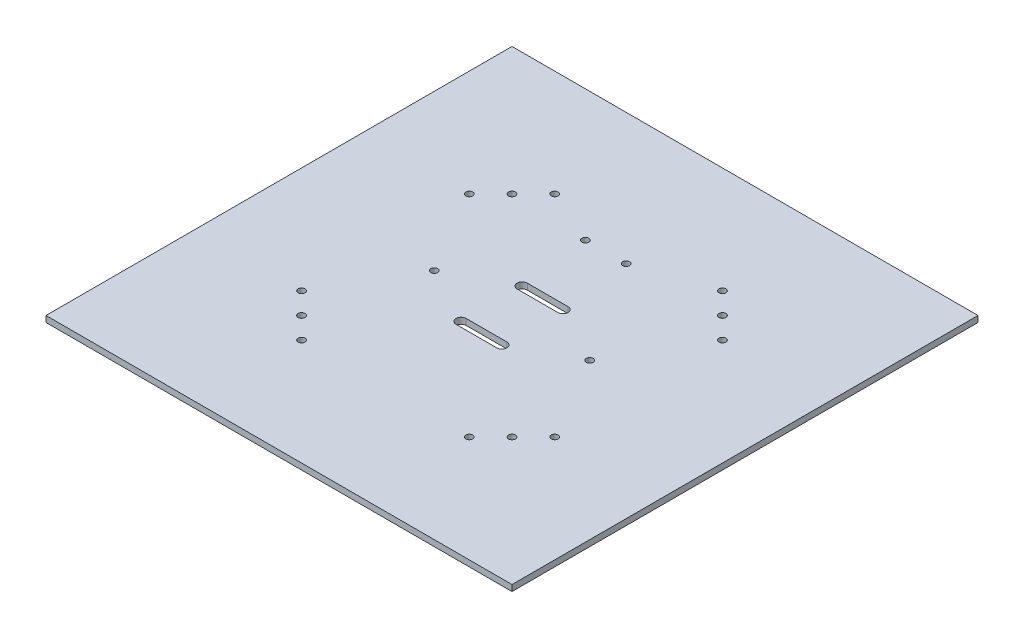
SolidWorks part; units mm, degrees
ref_plane "Front Plane" through (0, 0, 0) normal (0, 0, 1) x (1, 0, 0)
ref_plane "Top Plane" through (0, 0, 0) normal (0, 1, 0) x (1, 0, 0)
ref_plane "Right Plane" through (0, 0, 0) normal (1, 0, 0) x (0, 0, -1)
sketch "Sketch1" plane through (0, 0, 0) normal (0, 1, 0) x (1, 0, 0)
  line L1 (-114.3, 114.3) -> (114.3, 114.3)
  line L2 (-114.3, 114.3) -> (-114.3, -114.3)
  line L3 (-114.3, -114.3) -> (114.3, -114.3)
  line L4 (114.3, 114.3) -> (114.3, -114.3)
  line L5 (-114.3, 114.3) -> (114.3, -114.3) construction
  line L6 (-114.3, -114.3) -> (114.3, 114.3) construction
  point P0 (0, 0)
  dimension "D1" = 228.6
  dimension "D2" = 228.6
extrude "plate" add sketch "Sketch1" along normal blind 3
sketch "Sketch8" plane through (0, 3, 0) normal (0, 1, 0) x (1, 0, 0)
  line L0 (-114.3, 114.3) -> (114.3, -114.3) construction
  line L1 (114.3, 114.3) -> (-114.3, -114.3) construction
  line L2 (-62.6812, 165.9188) -> (165.9188, -62.6812) construction
  line L3 (0, 0) -> (51.6188, 51.6188) construction
  circle A0 centre (51.6188, 51.6188) radius 1.7
  circle A1 centre (62.084, 41.1536) radius 1.7
  circle A2 centre (41.1536, 62.084) radius 1.7
  circle A3 centre (51.6188, -51.6188) radius 1.7
  circle A4 centre (62.084, -41.1536) radius 1.7
  circle A5 centre (41.1536, -62.084) radius 1.7
  circle A6 centre (-51.6188, -51.6188) radius 1.7
  circle A7 centre (-41.1536, -62.084) radius 1.7
  circle A8 centre (-62.084, -41.1536) radius 1.7
  circle A9 centre (-51.6188, 51.6188) radius 1.7
  circle A10 centre (-62.084, 41.1536) radius 1.7
  circle A11 centre (-41.1536, 62.084) radius 1.7
  dimension "D2" = 3.4
  dimension "D3" = 3.4
  dimension "D4" = 3.4
  dimension "D5" = 14.8
  dimension "D6" = 14.8
  dimension "D8" = 73
  dimension "D9" = 73
  dimension "D1" = 73
  dimension "D7" = 4
extrude "motor-mount-holes" cut sketch "Sketch8" against normal blind 3
sketch "Sketch9" plane through (0, 3, 0) normal (0, 1, 0) x (1, 0, 0)
  line L0 (0, -114.3) -> (0, 114.3) construction
  line L2 (114.3, -114.3) -> (114.3, 114.3) construction
  line L3 (-114.3, 0) -> (114.3, 0) construction
  line L4 (114.3, 114.3) -> (-114.3, 114.3) construction
  line L5 (-114.3, -114.3) -> (114.3, -114.3) construction
  line L6 (-114.3, 114.3) -> (-114.3, -114.3) construction
  circle A0 centre (-38.13, 0) radius 1.7
  circle A1 centre (38.13, 0) radius 1.7
  point P3 (114.3, 130.3498)
  point P4 (0, 114.3)
  point P11 (0, 0)
  point P12 (0, 0)
  point P13 (-98.125, 98.125)
  point P14 (0, 0)
  point P19 (114.3, 0)
  point P20 (-43.9478, 158.2478)
  point P21 (0, 0)
  point P24 (-79.4235, 96.8618)
  point P25 (0, 0)
  point P26 (0, -114.3)
  point P29 (-114.3, 0)
  dimension "D3" = 3.4
  dimension "D4" = 3.4
  dimension "D1" = 76.26
  dimension "D2" = 38.13
extrude "connector-board-holes" cut sketch "Sketch9" against normal blind 3
sketch "Sketch11" plane through (0, 3, 0) normal (0, 1, 0) x (1, 0, 0)
  line L0 (-114.3, 0) -> (114.3, 0) construction
  line L1 (-114.3, 50) -> (114.3, 50) construction
  line L2 (0, -114.3) -> (0, 114.3) construction
  line L3 (27.5, -114.3) -> (27.5, 114.3) construction
  line L4 (-27.5, -114.3) -> (-27.5, 114.3) construction
  line L5 (-123.5172, 0) -> (114.3, 0) construction
  line L6 (-114.3, 114.3) -> (-114.3, -114.3) construction
  line L7 (114.3, -114.3) -> (114.3, 114.3) construction
  line L8 (0, -94.2235) -> (0, 114.3) construction
  line L9 (114.3, 114.3) -> (-114.3, 114.3) construction
  line L10 (-114.3, -114.3) -> (114.3, -114.3) construction
  line L11 (-123.5172, 50) -> (114.3, 50) construction
  line L12 (-27.5, -94.2235) -> (-27.5, 114.3) construction
  line L13 (27.5, -94.2235) -> (27.5, 114.3) construction
  circle A0 centre (-14, 50) radius 1.7
  circle A1 centre (6, 50) radius 1.7
  point P2 (114.3, 0)
  point P18 (-114.3, 0)
  point P22 (0, 0)
  point P23 (0, 0)
  point P24 (116.7614, 0)
  point P26 (0, 0)
  point P27 (0, 114.3)
  point P32 (0, 0)
  point P33 (0, -114.3)
  point P36 (-114.3, 50)
  point P38 (-27.5, 114.3)
  point P41 (-27.5, -114.3)
  point P42 (27.5, -114.3)
  point P44 (27.5, 114.3)
  dimension "D4" = 3.4
  dimension "D5" = 3.4
  dimension "D6" = 13.5
  dimension "D7" = 20
  dimension "D1" = 50
  dimension "D2" = 27.5
  dimension "D3" = 27.5
extrude "motor-controller-holder-arduino-holes" cut sketch "Sketch11" against normal up to next
sketch "Sketch12" plane through (0, 3, 0) normal (0, 1, 0) x (1, 0, 0)
  line L0 (114.3, 0) -> (-114.3, 0) construction
  line L1 (114.3, -114.3) -> (114.3, 114.3) construction
  line L2 (-114.3, 114.3) -> (-114.3, -114.3) construction
  line L3 (-10, 15) -> (10, 15) construction
  line L4 (-10, 17.5) -> (10, 17.5)
  line L5 (-10, 12.5) -> (10, 12.5)
  line L6 (-10, -15) -> (10, -15) construction
  line L7 (-10, -12.5) -> (10, -12.5)
  line L8 (-10, -17.5) -> (10, -17.5)
  line L9 (0, 114.3) -> (0, -114.3) construction
  line L10 (114.3, 114.3) -> (-114.3, 114.3) construction
  line L11 (-114.3, -114.3) -> (114.3, -114.3) construction
  arc A0 (-10, 17.5) -> (-10, 12.5) centre (-10, 15) ccw
  arc A1 (10, 12.5) -> (10, 17.5) centre (10, 15) ccw
  arc A2 (-10, -12.5) -> (-10, -17.5) centre (-10, -15) ccw
  arc A3 (10, -17.5) -> (10, -12.5) centre (10, -15) ccw
  point P8 (0, 15)
  point P13 (0, -15)
  point P20 (0, 15)
  point P21 (0, -15)
  point P28 (0, 15)
  point P29 (-4.2503, 15)
  point P30 (0, 0)
  dimension "D5" = 2.5
  dimension "D6" = 2.5
  dimension "D1" = 15
  dimension "D2" = 15
  dimension "D3" = 20
  dimension "D4" = 20
extrude "cable-slots" cut sketch "Sketch12" against normal up to next
sketch "Sketch10" plane through (0, 3, 0) normal (0, 1, 0) x (1, 0, 0)
  line L0 (0, 114.3) -> (0, -114.3) construction
  line L1 (114.3, 114.3) -> (-114.3, 114.3) construction
  line L2 (-114.3, -114.3) -> (114.3, -114.3) construction
  line L3 (-114.3, 0) -> (114.3, 0) construction
  line L4 (-114.3, 114.3) -> (-114.3, -114.3) construction
  line L5 (114.3, -114.3) -> (114.3, 114.3) construction
  line L6 (0, 0) -> (0, 62.08) construction
  circle A1 centre (0, 62.08) radius 1.7
  circle A2 centre (62.08, 0) radius 1.7
  circle A3 centre (0, -62.08) radius 1.7
  circle A4 centre (-62.08, 0) radius 1.7
  dimension "D1" = 3.4
  dimension "D2" = 62.08
  dimension "D4" = 62.08
  dimension "D5" = 62.08
  dimension "D3" = 4
extrude "level2-standoff-holes" [suppressed] cut sketch "Sketch10" against normal blind 3
sketch "Sketch2" plane through (0, 3, 0) normal (0, 1, 0) x (1, 0, 0)
  line L0 (-114.3, -114.3) -> (114.3, 114.3) construction
  line L1 (114.3, -114.3) -> (-114.3, 114.3) construction
  line L2 (-96.3395, -132.2605) -> (132.2605, 96.3395) construction
  line L3 (-132.2605, -96.3395) -> (96.3395, 132.2605) construction
  line L4 (186.142, -42.458) -> (-42.458, 186.142) construction
  line L5 (114.3, 114.3) -> (78.379, 114.3)
  line L6 (114.3, 114.3) -> (-114.3, 114.3) construction
  line L7 (78.379, 114.3) -> (53.8815, 89.8026)
  line L8 (53.8815, 89.8026) -> (89.8026, 53.8815)
  line L9 (89.8026, 53.8815) -> (114.3, 78.379)
  line L10 (114.3, 78.379) -> (114.3, 114.3)
  line L11 (78.379, -114.3) -> (114.3, -114.3)
  line L12 (114.3, -114.3) -> (114.3, -78.379)
  line L13 (114.3, -78.379) -> (89.8026, -53.8815)
  line L14 (89.8026, -53.8815) -> (53.8815, -89.8026)
  line L15 (53.8815, -89.8026) -> (78.379, -114.3)
  line L16 (-114.3, -78.379) -> (-114.3, -114.3)
  line L17 (-114.3, -114.3) -> (-78.379, -114.3)
  line L18 (-78.379, -114.3) -> (-53.8815, -89.8026)
  line L19 (-53.8815, -89.8026) -> (-89.8026, -53.8815)
  line L20 (-89.8026, -53.8815) -> (-114.3, -78.379)
  line L21 (-78.379, 114.3) -> (-114.3, 114.3)
  line L22 (-114.3, 114.3) -> (-114.3, 78.379)
  line L23 (-114.3, 78.379) -> (-89.8026, 53.8815)
  line L24 (-89.8026, 53.8815) -> (-53.8815, 89.8026)
  line L25 (-53.8815, 89.8026) -> (-78.379, 114.3)
  line L26 (0, 0) -> (89.8026, 53.8815) construction
  line L27 (0, 0) -> (53.8815, -89.8026) construction
  dimension "D5" = 90
  dimension "D6" = 14.036
  dimension "D7" = 104.7269
  dimension "D1" = 25.4
  dimension "D2" = 25.4
  dimension "D3" = 101.6
  dimension "D4" = 4
extrude "wheel-slots" [suppressed] cut sketch "Sketch2" against normal blind 3
